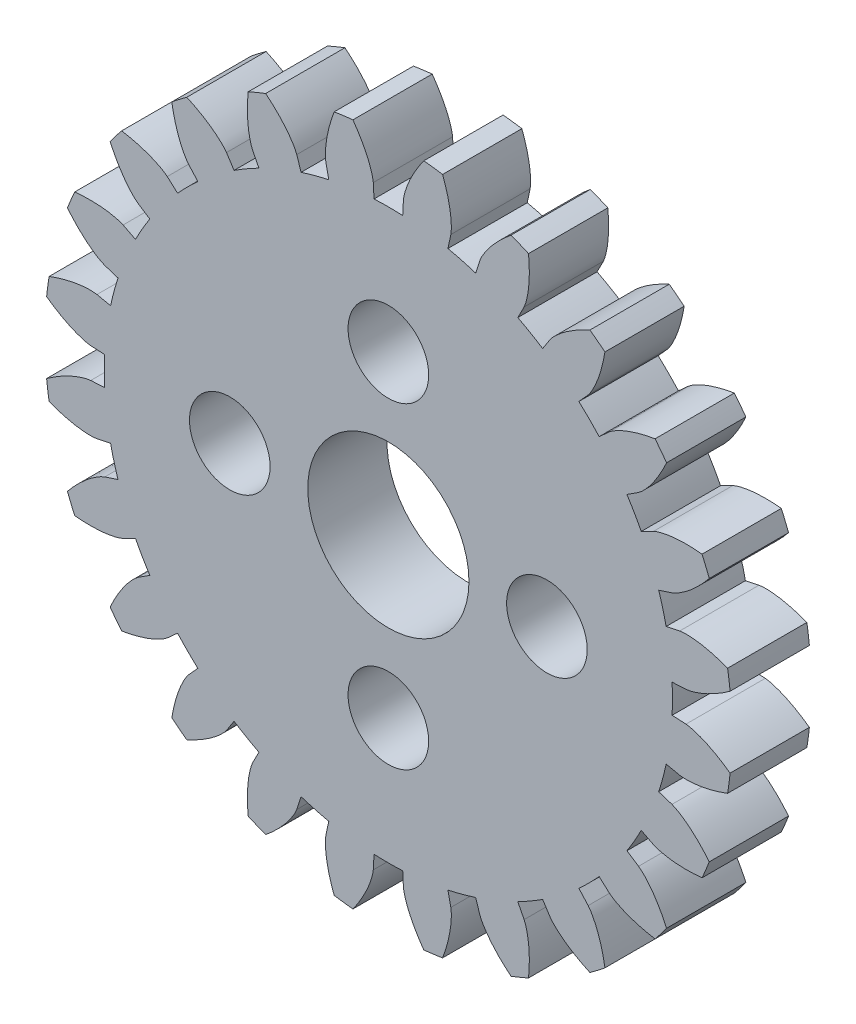
SolidWorks part; units mm, degrees
ref_plane "正面" through (0, 0, 0) normal (0, 0, 1) x (1, 0, 0)
ref_plane "平面" through (0, 0, 0) normal (0, 1, 0) x (1, 0, 0)
ref_plane "右側面" through (0, 0, 0) normal (1, 0, 0) x (0, 0, -1)
sketch "インボリュート スケッチ" plane through (0, 0, 0) normal (0, 0, 1) x (1, 0, 0)
  line L0 (-34.8106, -13.0518) -> (0.5697, -11.2619)
  line L1 (0.5697, -11.2619) -> (-0.5697, 11.2619) construction
  line L2 (0, 0) -> (0, 13) construction
  line L3 (-0.5697, 11.2619) -> (-0.5431, 10.7363)
  line L4 (0, 0) -> (0.5697, -11.2619)
  line L5 (-0.5431, 10.7363) -> (0, 10.7363)
  line L6 (0, 10.7363) -> (0, 0)
  circle A0 centre (0, 0) radius 11.2763 construction
  circle A1 centre (0, 0) radius 12 construction
  circle A2 centre (0, 0) radius 10.75 construction
  circle A3 centre (0, 0) radius 13 construction
  spline S0 degree 4 poles (-0.5697, 11.2619) (-0.574, 11.3046) (-0.5866, 11.3894) (-0.6249, 11.5484) (-0.6996, 11.7771) (-0.8595, 12.1613) (-1.1813, 12.7395) (-1.7152, 13.4541) (-2.5966, 14.3353) (-3.7723, 15.202) (-5.1872, 15.9587) (-6.8096, 16.5558) (-8.4923, 16.9475) (-10.208, 17.1468) (-12.02, 17.1664) (-14.2543, 16.9568) (-16.8688, 16.3668) (-19.7751, 15.2449) (-22.7719, 13.5148) (-25.4876, 11.3728) (-27.8885, 8.8847) (-29.6939, 6.4582) (-31.0213, 4.2351) (-31.9784, 2.3033) (-32.654, 0.7163) (-33.2393, -0.9057) (-33.7343, -2.5583) (-34.2406, -4.6529) (-34.5976, -6.7819) (-34.7866, -8.711) (-34.849, -10.3301) (-34.8576, -11.1858) (-34.8531, -11.7695) (-34.8449, -12.2259) (-34.821, -12.8723) (-34.7957, -13.354) (-34.7427, -14.1461) (-34.6848, -14.7539) (-34.6065, -15.4973) (-34.5193, -16.1547) (-34.4161, -16.8643) (-34.3018, -17.534) (-34.2052, -18.0593) (-34.1373, -18.3928) (-34.1019, -18.5662) knots 0 0 0 0 0 0.002802 0.005604 0.010661 0.015718 0.02996 0.048734 0.068727 0.096889 0.125051 0.153212 0.181374 0.209535 0.237696 0.271429 0.327752 0.384075 0.440398 0.496721 0.553044 0.609367 0.637529 0.66569 0.693852 0.722013 0.750174 0.778336 0.834659 0.86282 0.876901 0.883942 0.890982 0.900036 0.909091 0.920455 0.931818 0.943182 0.954545 0.965909 0.977273 0.988636 1 1 1 1 1 construction
  spline S1 degree 4 poles (-0.5697, 11.2619) (-0.574, 11.3046) (-0.5866, 11.3894) (-0.6249, 11.5484) (-0.6996, 11.7771) (-0.8595, 12.1613) (-1.1813, 12.7395) (-1.7152, 13.4541) (-2.5966, 14.3353) (-3.7723, 15.202) (-5.1872, 15.9587) (-6.8096, 16.5558) (-8.4923, 16.9475) (-10.208, 17.1468) (-12.02, 17.1664) (-14.2543, 16.9568) (-16.8688, 16.3668) (-19.7751, 15.2449) (-22.7719, 13.5148) (-25.4876, 11.3728) (-27.8885, 8.8847) (-29.6939, 6.4582) (-31.0213, 4.2351) (-31.9784, 2.3033) (-32.654, 0.7163) (-33.2393, -0.9057) (-33.7343, -2.5583) (-34.2406, -4.6529) (-34.5976, -6.7819) (-34.7866, -8.711) (-34.849, -10.3301) (-34.8576, -11.1858) (-34.8531, -11.7695) (-34.8449, -12.2259) (-34.8284, -12.6711) (-34.817, -12.926) (-34.8106, -13.0518) knots 0 0 0 0 0 0.002802 0.005604 0.010661 0.015718 0.02996 0.048734 0.068727 0.096889 0.125051 0.153212 0.181374 0.209535 0.237696 0.271429 0.327752 0.384075 0.440398 0.496721 0.553044 0.609367 0.637529 0.66569 0.693852 0.722013 0.750174 0.778336 0.834659 0.86282 0.876901 0.883942 0.890982 0.900036 0.909091 0.909091 0.909091 0.909091 0.909091
  point P6 (-0.7848, 11.9743)
  point P12 (0, 12)
  point P24 (0, 0)
  dimension "D1" = 22.5526
  dimension "D2" = 24
  dimension "D3" = 21.5
  dimension "D4" = 26
  dimension "D5" = 0.7854
extrude "インボリュート ボス" add sketch "インボリュート スケッチ" along normal blind 3
mirror "インボリュート ミラー" about plane through (0, 0, 3) normal (1, 0, 0) of bodies 161
sketch "歯先円 スケッチ" plane through (0, 0, 3) normal (0, 0, 1) x (1, 0, 0)
  circle A0 centre (0, 0) radius 37.177
  circle A1 centre (0, 0) radius 13
  dimension "D1" = 26
extrude "歯先円 カット" cut sketch "歯先円 スケッチ" against normal through all
sketch "歯分割 スケッチ" plane through (0, 0, 3) normal (0, 0, 1) x (1, 0, 0)
  line L0 (-1.6968, 12.8888) -> (0, 0)
  line L1 (0, 0) -> (1.6968, 12.8888)
  line L2 (0, 0) -> (0, 12) construction
  arc A0 (-1.6968, 12.8888) -> (1.6968, 12.8888) centre (0, 0) ccw
  circle A2 centre (0, 0) radius 12 construction
  arc A3 (-1.3415, 12.9306) -> (-5.8908, -11.5887) centre (0, 0) ccw construction
  point P9 (-1.5663, 11.8973)
  point P10 (1.5663, 11.8973)
  dimension "D1" = 24
  dimension "D2" = 3.1416
extrude "歯分割 カット" cut sketch "歯分割 スケッチ" against normal through all
pattern_circular "歯分割 円形コピー" count 24 over 360 about axis through (0, 0, 0) along (0, 0, 1) of bodies 166
sketch "歯底円 スケッチ" plane through (0, 0, 3) normal (0, 0, 1) x (1, 0, 0)
  circle A0 centre (0, 0) radius 10.75
  dimension "D1" = 21.5
extrude "歯底円 ボス" add sketch "歯底円 スケッチ" against normal through all
sketch "軸 丸穴 スケッチ" plane through (0, 0, 3) normal (0, 0, 1) x (1, 0, 0)
  circle A0 centre (0, 0) radius 3.05
  dimension "D1" = 6.1
extrude "軸 丸穴 カット" cut sketch "軸 丸穴 スケッチ" against normal through all
sketch "軸 キー溝 スケッチ" plane through (0, 0, 3) normal (0, 0, 1) x (1, 0, 0)
  line L2 (-1.5, 3.7081) -> (-1.5, 5.4)
  line L3 (-1.5, 5.4) -> (1.5, 5.4)
  line L4 (1.5, 3.7081) -> (1.5, 5.4)
  arc A0 (-1.5, 3.7081) -> (1.5, 3.7081) centre (0, 0) ccw
  dimension "D1" = 8
  dimension "D2" = 3
  dimension "D3" = 5.4
extrude "軸 キー溝 カット" [suppressed] cut sketch "軸 キー溝 スケッチ" against normal through all
sketch "軸 Dカット スケッチ" plane through (0, 0, 3) normal (0, 0, 1) x (1, 0, 0)
  line L0 (-1.9861, 2) -> (1.9861, 2)
  arc A0 (-2.3948, 1.8069) -> (2.3948, 1.8069) centre (0, 0) ccw
  arc A1 (-1.9861, 2) -> (-2.3948, 1.8069) centre (-2.2361, 2) ccw
  arc A2 (2.3948, 1.8069) -> (1.9861, 2) centre (2.2361, 2) ccw
  dimension "D1" = 6
  dimension "D3" = 0.5
  dimension "D2" = 2
extrude "軸 Dカット カット" [suppressed] cut sketch "軸 Dカット スケッチ" against normal through all
sketch "軸 角穴 スケッチ" plane through (0, 0, 3) normal (0, 0, 1) x (1, 0, 0)
  line L0 (-5.1, 5.1) -> (5.1, 5.1)
  line L1 (-5, -5) -> (5, -5) construction
  line L2 (-5, -5) -> (-5, 5) construction
  line L3 (-5, 5) -> (5, 5) construction
  line L4 (5, -5) -> (5, 5) construction
  line L5 (-5, -5) -> (5, 5) construction
  line L6 (-5, 5) -> (5, -5) construction
  line L7 (5.1, -5.1) -> (5.1, 5.1)
  line L8 (-5.1, -5.1) -> (5.1, -5.1)
  line L9 (-5.1, -5.1) -> (-5.1, 5.1)
  point P0 (0, 0)
  dimension "D1" = 10
  dimension "D2" = 0.1
extrude "軸 角穴 カット" [suppressed] cut sketch "軸 角穴 スケッチ" against normal through all
sketch "フランジ穴 スケッチ" plane through (0, 0, 3) normal (0, 0, 1) x (1, 0, 0)
  circle A0 centre (0, 12) radius 1.6
  circle A1 centre (12, 0) radius 1.6
  circle A2 centre (0, -12) radius 1.6
  circle A3 centre (-12, 0) radius 1.6
  point P12 (0, 0)
  dimension "D2" = 3.2
  dimension "D3" = 12
  dimension "D1" = 4
extrude "フランジ穴 カット" [suppressed] cut sketch "フランジ穴 スケッチ" against normal through all
sketch "合致用スケッチ" plane through (0, 0, 3) normal (0, 0, 1) x (1, 0, 0)
  line L0 (0, 0) -> (0, 12)
  line L1 (0, 0) -> (1.5663, 11.8973)
  line L2 (0, 0) -> (4.5922, 11.0866)
  line L3 (0, 0) -> (7.3051, 9.5202)
  line L4 (0, 0) -> (9.5202, 7.3051)
  line L5 (0, 0) -> (11.0866, 4.5922)
  line L6 (0, 0) -> (11.8973, 1.5663)
  line L7 (0, 0) -> (11.8973, -1.5663)
  line L8 (0, 0) -> (11.0866, -4.5922)
  line L9 (0, 0) -> (9.5202, -7.3051)
  line L10 (0, 0) -> (7.3051, -9.5202)
  line L11 (0, 0) -> (4.5922, -11.0866)
  line L12 (0, 0) -> (1.5663, -11.8973)
  line L13 (0, 0) -> (-1.5663, -11.8973)
  line L14 (0, 0) -> (-4.5922, -11.0866)
  line L15 (0, 0) -> (-7.3051, -9.5202)
  line L16 (0, 0) -> (-9.5202, -7.3051)
  line L17 (0, 0) -> (-11.0866, -4.5922)
  line L18 (0, 0) -> (-11.8973, -1.5663)
  line L19 (0, 0) -> (-11.8973, 1.5663)
  line L20 (0, 0) -> (-11.0866, 4.5922)
  line L21 (0, 0) -> (-9.5202, 7.3051)
  line L22 (0, 0) -> (-7.3051, 9.5202)
  line L23 (0, 0) -> (-4.5922, 11.0866)
  line L24 (0, 0) -> (-1.5663, 11.8973)
  circle A2 centre (0, 0) radius 12
  point P30 (0, 0)
  dimension "D1" = 24
  dimension "D2" = 7.5
  dimension "D3" = 24
sketch "ｽｹｯﾁ1" plane through (0, 0, 3) normal (0, 0, 1) x (1, 0, 0)
  line L0 (0, 0) -> (6, 0) construction
  line L1 (0, 0) -> (0, -6) construction
  line L2 (0, 0) -> (-6, 0) construction
  line L3 (0, 0) -> (0, 6) construction
  circle A0 centre (6, 0) radius 1.525
  circle A1 centre (0, -6) radius 1.525
  circle A2 centre (-6, 0) radius 1.525
  circle A3 centre (0, 6) radius 1.525
  point P12 (0, 0)
  dimension "D1" = 3.05
  dimension "D2" = 6
  dimension "D3" = 4
extrude "ｶｯﾄ - 押し出し1" cut sketch "ｽｹｯﾁ1" against normal through all
equation "\"モジュール\"= 1"
equation "\"基準圧力角\"= 20"
equation "\"歯数\"= 24"
equation "\"基準円直径\"= \"歯数\" * \"モジュール\""
equation "\"基礎円直径\"= \"基準円直径\" * cos ( \"基準圧力角\" )"
equation "\"歯先円直径\"= \"基準円直径\" + 2 * \"モジュール\""
equation "\"歯底円直径\"= \"基準円直径\" - 2.5 * \"モジュール\""
equation "\"D1@インボリュート スケッチ\" = \"基礎円直径\""
equation "\"D2@インボリュート スケッチ\" = \"基準円直径\""
equation "\"D3@インボリュート スケッチ\" = \"歯底円直径\""
equation "\"D4@インボリュート スケッチ\" = \"歯先円直径\""
equation "\"D5@インボリュート スケッチ\" = Pi * \"モジュール\" / 4"
equation "\"D1@歯先円 スケッチ\" = \"歯先円直径\""
equation "\"D1@歯分割 スケッチ\" = \"基準円直径\""
equation "\"D2@歯分割 スケッチ\" = PI * \"モジュール\""
equation "\"D1@歯分割 円形コピー\" = \"歯数\""
equation "\"D1@歯底円 スケッチ\" = \"歯底円直径\""
equation "\"板厚\"= 3"
equation "\"D1@インボリュート ボス\"=\"板厚\""
equation "\"D1@合致用スケッチ\" = \"基準円直径\""
equation "\"D2@合致用スケッチ\"=180/\"歯数\""
